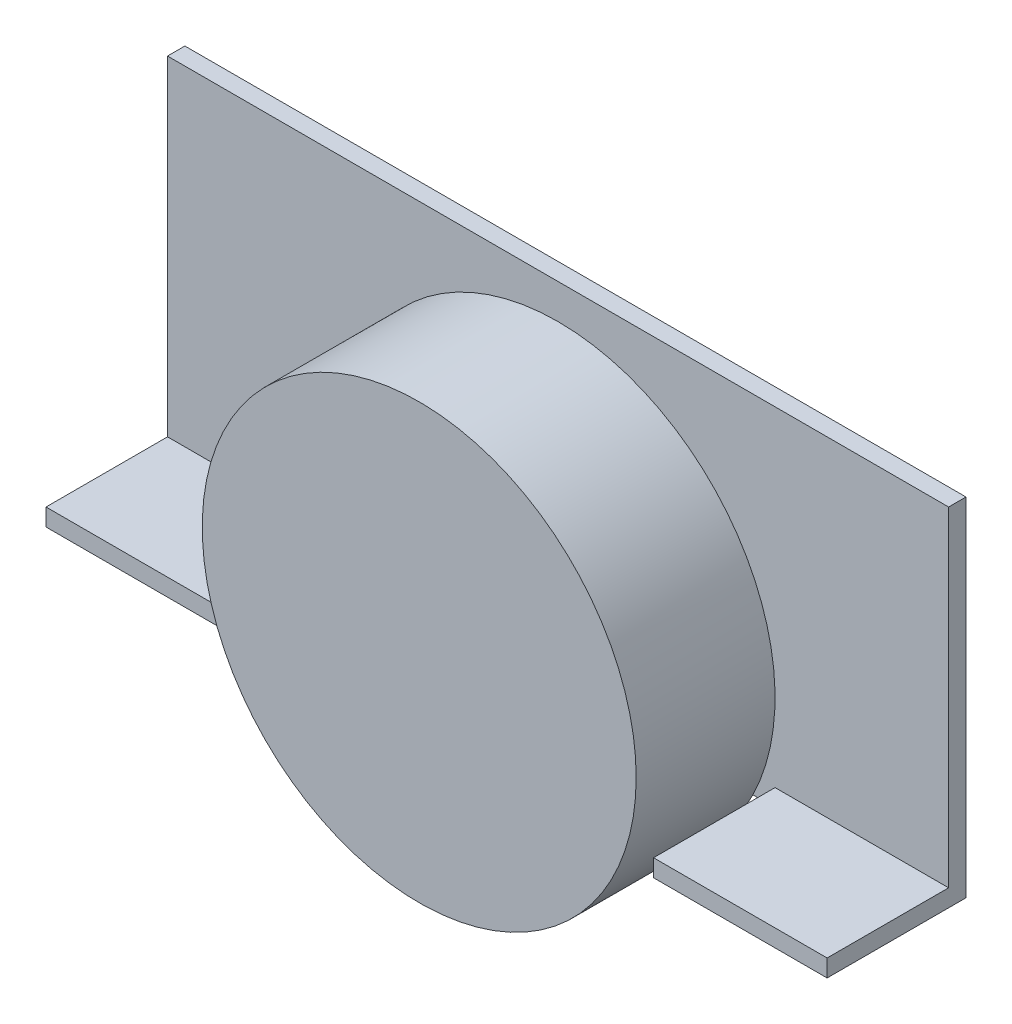
SolidWorks part; units mm, degrees
ref_plane "Front Plane" through (0, 0, 0) normal (0, 0, 1) x (1, 0, 0)
ref_plane "Top Plane" through (0, 0, 0) normal (0, 1, 0) x (1, 0, 0)
ref_plane "Right Plane" through (0, 0, 0) normal (1, 0, 0) x (0, 0, -1)
sketch "Sketch2" plane through (0, 0, 0) normal (0, 0, 1) x (1, 0, 0)
  line L1 (0, 0) -> (45, 0)
  line L2 (0, 0) -> (0, 20)
  line L3 (0, 20) -> (45, 20)
  line L4 (45, 0) -> (45, 20)
  point P5 (0, 0)
  dimension "D1" = 45
  dimension "D2" = 20
extrude "Boss-Extrude1" add sketch "Sketch2" along normal blind 1
sketch "Sketch3" plane through (0, 0, 1) normal (0, 0, 1) x (1, 0, 0)
  line L0 (45, 20) -> (0, 20) construction
  line L1 (0, 0) -> (45, 0) construction
  circle A0 centre (22.5, 5.5) radius 12.5
  point P6 (22.5, 0)
  dimension "D1" = 25
  dimension "D2" = 14.5
extrude "Boss-Extrude4" add sketch "Sketch3" along normal blind 8 contours A0
sketch "Sketch6" plane through (0, 0, 1) normal (0, 0, 1) x (1, 0, 0)
  line L1 (0, 0) -> (10, 0)
  line L2 (0, 0) -> (0, 1)
  line L3 (0, 1) -> (10, 1)
  line L4 (10, 0) -> (10, 1)
  line L5 (45, 0) -> (35, 0)
  line L6 (45, 0) -> (45, 1)
  line L7 (45, 1) -> (35, 1)
  line L8 (35, 0) -> (35, 1)
  dimension "D1" = 10
  dimension "D2" = 1
  dimension "D3" = 10
  dimension "D4" = 1
extrude "Boss-Extrude5" add sketch "Sketch6" along normal blind 7
